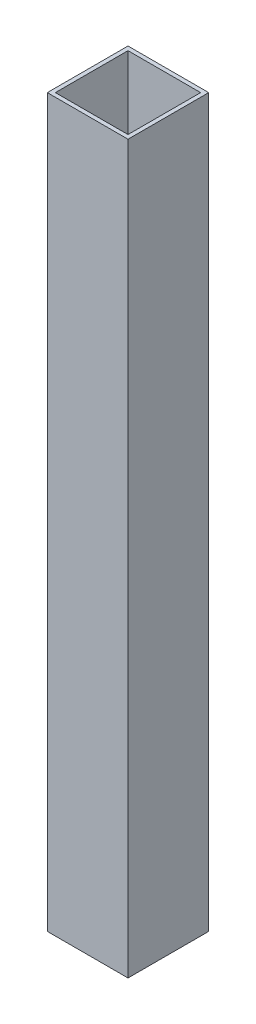
SolidWorks part; units mm, degrees
material "Alloy Steel"
ref_plane "Front Plane" through (0, 0, 0) normal (0, 0, 1) x (1, 0, 0)
ref_plane "Top Plane" through (0, 0, 0) normal (0, 1, 0) x (1, 0, 0)
ref_plane "Right Plane" through (0, 0, 0) normal (1, 0, 0) x (0, 0, -1)
sketch "Sketch1" plane through (0, 0, 0) normal (0, 0, 1) x (1, 0, 0)
  line L1 (0, 0) -> (50.8, 0)
  line L2 (0, 0) -> (0, -457.2)
  line L3 (0, -457.2) -> (50.8, -457.2)
  line L4 (50.8, 0) -> (50.8, -457.2)
  dimension "D1" = 50.8
  dimension "D2" = 457.2
extrude "Boss-Extrude1" add sketch "Sketch1" along normal blind 50.8
shell "Shell1" thickness 2.54
sketch "Sketch2" plane through (0, -457.2, 0) normal (0, -1, 0) x (1, 0, 0)
  line L0 (48.26, 48.26) -> (2.54, 48.26)
  line L1 (2.54, 48.26) -> (2.54, 2.54)
  line L2 (2.54, 2.54) -> (48.26, 2.54)
  line L3 (48.26, 2.54) -> (48.26, 48.26)
extrude "Cut-Extrude1" cut sketch "Sketch2" against normal blind 50.8
